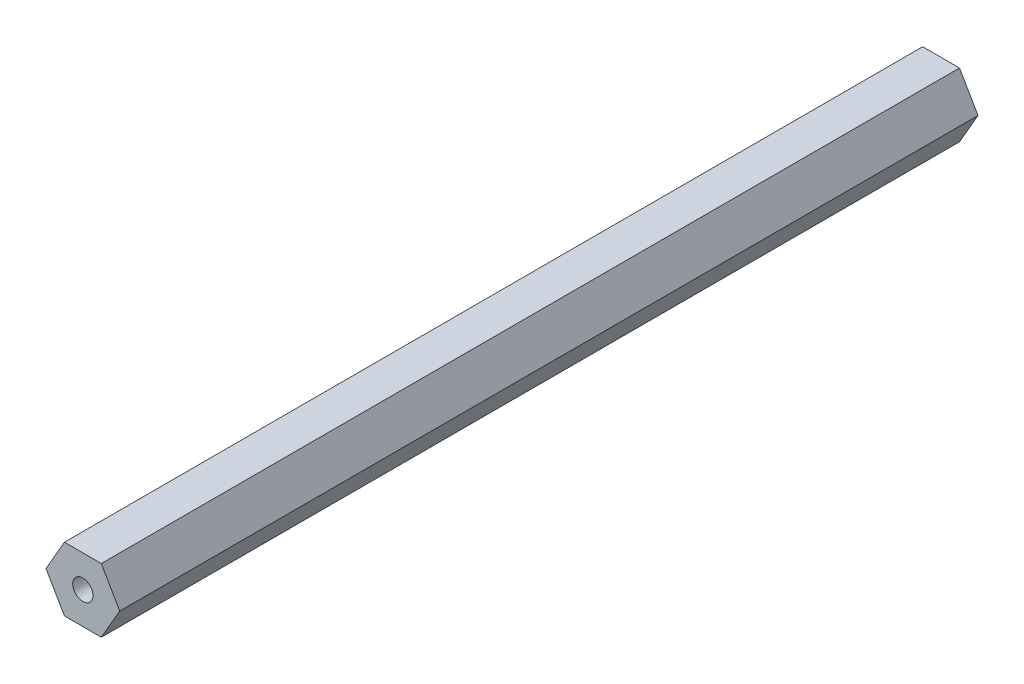
SolidWorks part; units mm, degrees
material "6061 Alloy"
ref_plane "Front Plane" through (0, 0, 0) normal (0, 0, 1) x (1, 0, 0)
ref_plane "Top Plane" through (0, 0, 0) normal (0, 1, 0) x (1, 0, 0)
ref_plane "Right Plane" through (0, 0, 0) normal (1, 0, 0) x (0, 0, -1)
sketch "Sketch1" plane through (0, 0, 0) normal (0, 0, 1) x (1, 0, 0)
  line L1 (7.3323, 0) -> (3.6662, 6.35)
  line L2 (3.6662, 6.35) -> (-3.6662, 6.35)
  line L3 (-3.6662, 6.35) -> (-7.3323, 0)
  line L4 (-7.3323, 0) -> (-3.6662, -6.35)
  line L5 (-3.6662, -6.35) -> (3.6662, -6.35)
  line L6 (3.6662, -6.35) -> (7.3323, 0)
  circle A0 centre (0, 0) radius 6.35 construction
  circle A1 centre (0, 0) radius 2.0193
  dimension "D1" = 12.7
  dimension "D2" = 4.0386
extrude "Boss-Extrude1" add sketch "Sketch1" along normal blind 170.6562
